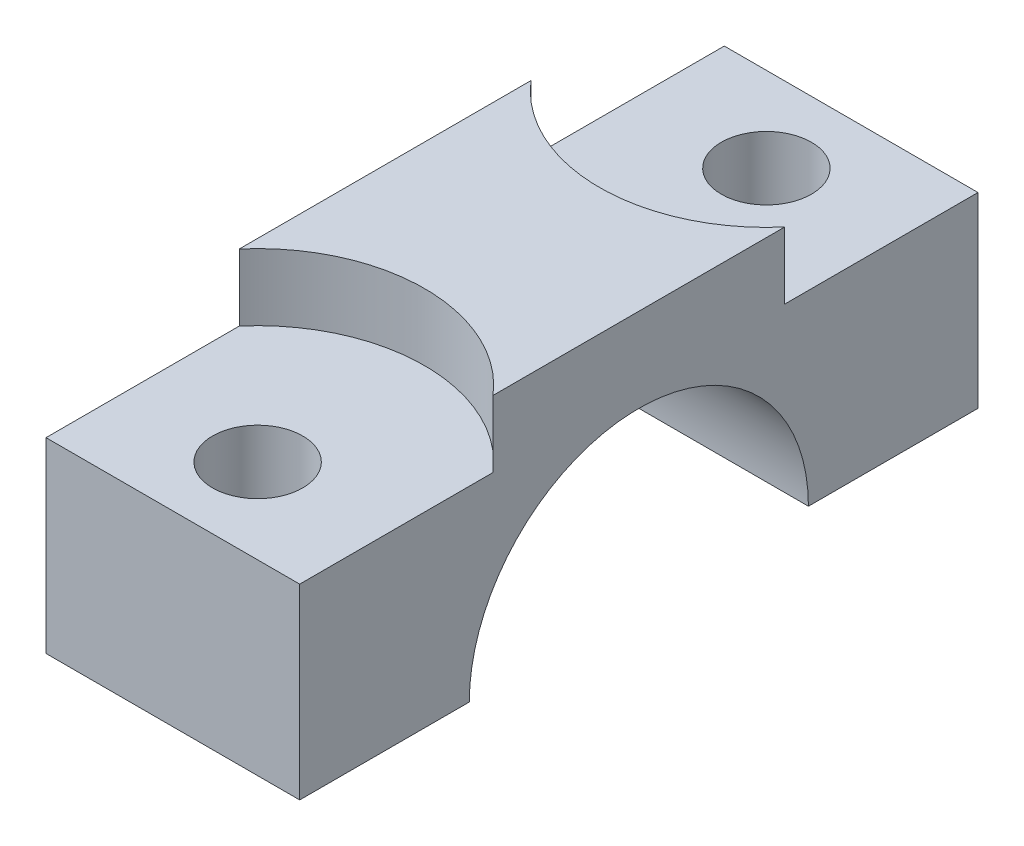
SolidWorks part; units mm, degrees
ref_plane "Front Plane" through (0, 0, 0) normal (0, 0, 1) x (1, 0, 0)
ref_plane "Top Plane" through (0, 0, 0) normal (0, 1, 0) x (1, 0, 0)
ref_plane "Right Plane" through (0, 0, 0) normal (1, 0, 0) x (0, 0, -1)
sketch "Sketch1" plane through (0, 0, 0) normal (1, 0, 0) x (0, 0, -1)
  line L9 (-25.4, 19) -> (25.4, 19)
  line L10 (-25.4, 19) -> (-25.4, 0)
  line L11 (-25.4, 0) -> (25.4, 0)
  line L12 (25.4, 19) -> (25.4, 0)
  circle A0 centre (0, 0) radius 12.7
  dimension "D1" = 25.4
  dimension "D2" = 19
  dimension "D3" = 50.8
extrude "Boss-Extrude1" add sketch "Sketch1" along normal mid plane 19 contours A0 L11 L12 L9 L10
sketch "Sketch2" plane through (0, 0, 0) normal (0, -1, 0) x (1, 0, 0)
  line L0 (0, 25.4) -> (0, 12.7) construction
  line L1 (9.5, 25.4) -> (-9.5, 25.4) construction
  line L2 (9.5, 12.7) -> (-9.5, 12.7) construction
  line L3 (0, -12.7) -> (0, -25.4) construction
  line L4 (9.5, -12.7) -> (-9.5, -12.7) construction
  line L5 (9.5, -25.4) -> (-9.5, -25.4) construction
  point P12 (0, 19.05)
  point P13 (0, -19.05)
hole_wizard "CBORE for M12 Hex Head Cap Screw1" positions "Sketch3" profile "Sketch4" counterbore size "M12" standard "ISO" end condition through all
sketch "Sketch3" plane through (0, 19, 0) normal (0, 1, 0) x (1, 0, 0)
  point P3 (0, -19.05)
  point P6 (0, 19.05)
sketch "Sketch4" plane through (0, 19, 19.05) normal (1, 0, 0) x (0, 0, 1)
  line L0 (0, 0) -> (0, 19)
  line L1 (0, 19) -> (3.375, 19)
  line L3 (3.375, 19) -> (3.375, 5)
  line L4 (3.375, 5) -> (12.5, 5)
  line L5 (12.5, 5) -> (12.5, 0)
  line L7 (12.5, 0) -> (0, 0)
  line L11 (0, -6.35) -> (0, 107.95) construction
  dimension "Thru Hole Dia." = 6.75
  dimension "Thru Hole Depth" = 19
  dimension "C'Bore Dia." = 25
  dimension "C'Bore Depth" = 5
